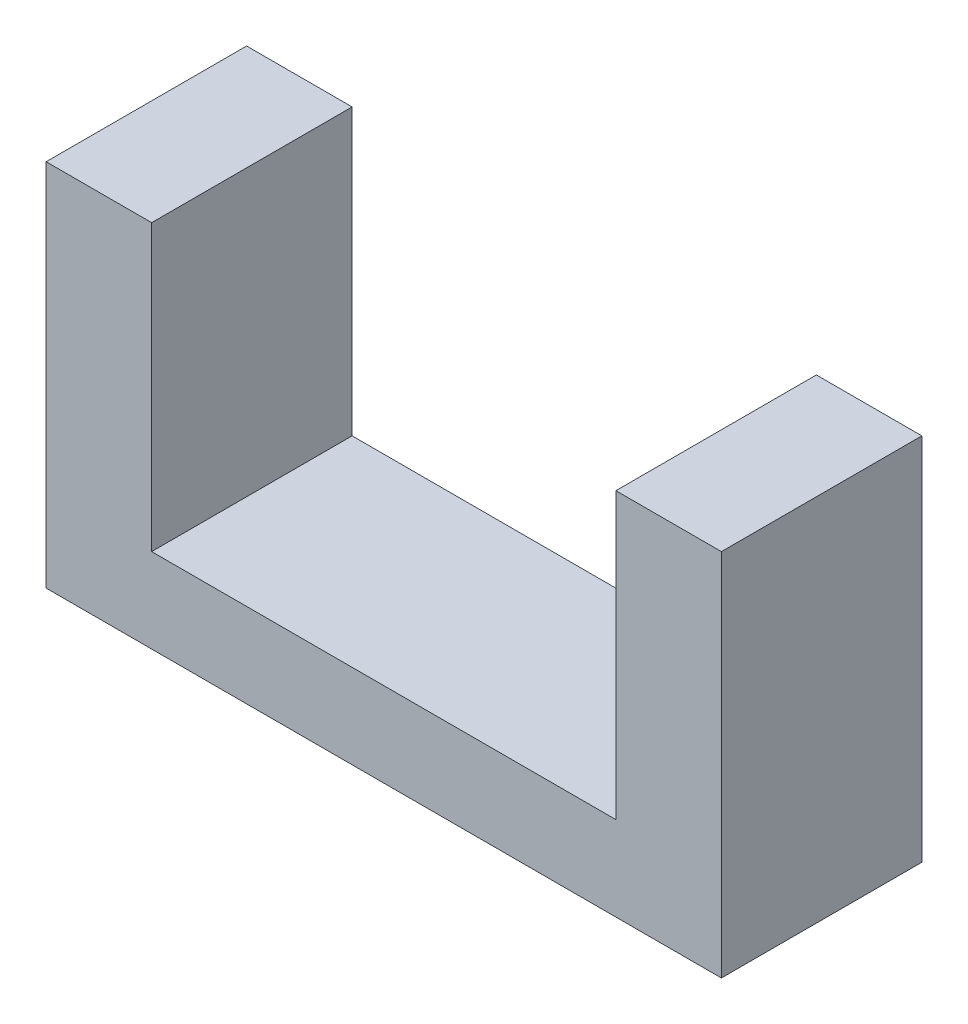
SolidWorks part; units mm, degrees
ref_plane "前视基准面" through (0, 0, 0) normal (0, 0, 1) x (1, 0, 0)
ref_plane "上视基准面" through (0, 0, 0) normal (0, 1, 0) x (1, 0, 0)
ref_plane "右视基准面" through (0, 0, 0) normal (1, 0, 0) x (0, 0, -1)
sketch "草图1" plane through (0, 0, 0) normal (0, 1, 0) x (1, 0, 0)
  line L1 (0, 0) -> (32, 0)
  line L2 (0, 0) -> (0, -9.5)
  line L3 (0, -9.5) -> (32, -9.5)
  line L4 (32, 0) -> (32, -9.5)
  dimension "D1" = 32
  dimension "D2" = 9.5
extrude "凸台-拉伸1" add sketch "草图1" along normal blind 4
sketch "草图2" plane through (0, 4, 0) normal (0, 1, 0) x (1, 0, 0)
  line L0 (0, -9.5) -> (32, -9.5) construction
  line L1 (0, 0) -> (5, 0)
  line L2 (0, 0) -> (0, -9.5)
  line L3 (0, -9.5) -> (5, -9.5)
  line L4 (5, 0) -> (5, -9.5)
  dimension "D1" = 5
extrude "凸台-拉伸2" add sketch "草图2" along normal blind 13.5
sketch "草图3" plane through (0, 4, 0) normal (0, 1, 0) x (1, 0, 0)
  line L0 (5, -9.5) -> (32, -9.5) construction
  line L1 (32, 0) -> (27, 0)
  line L2 (32, 0) -> (32, -9.5)
  line L3 (32, -9.5) -> (27, -9.5)
  line L4 (27, 0) -> (27, -9.5)
  dimension "D1" = 5
extrude "凸台-拉伸3" add sketch "草图3" along normal blind 13.5
